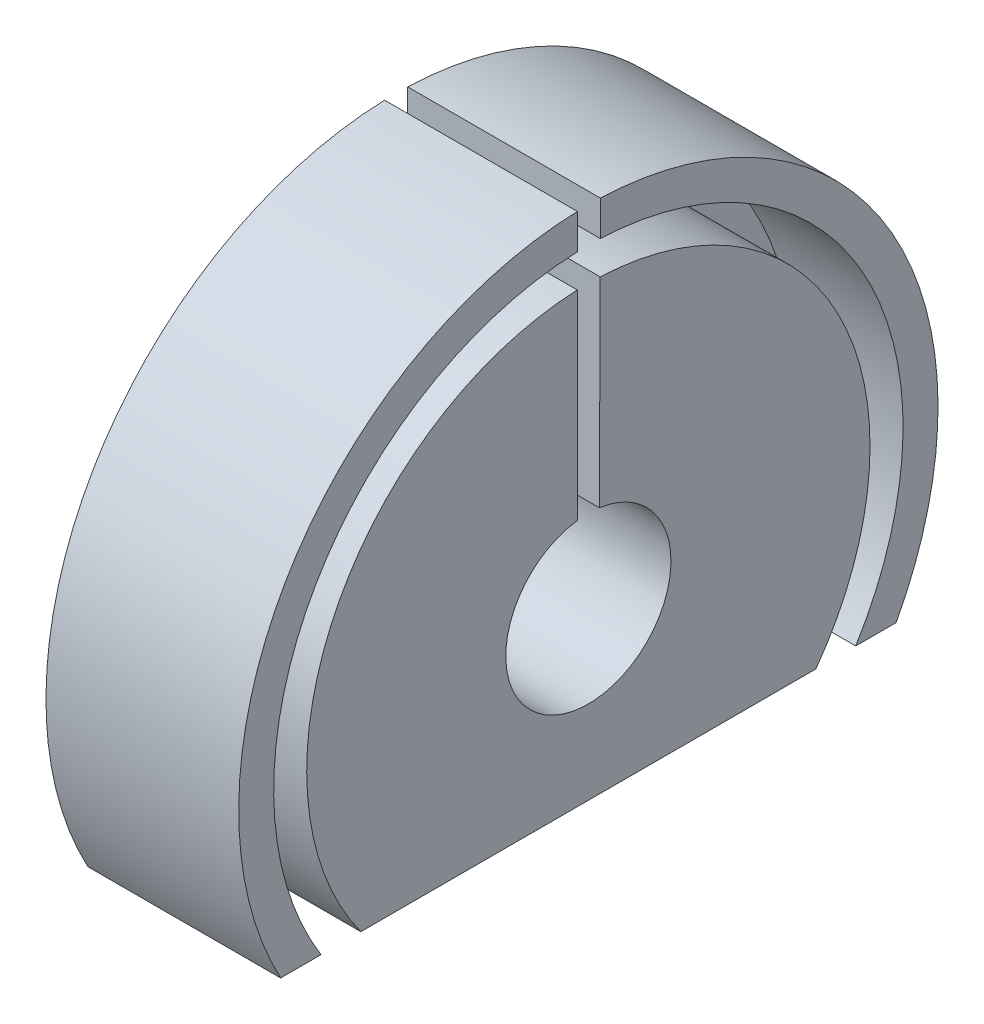
SolidWorks part; units mm, degrees
ref_plane "Front" through (0, 0, 0) normal (0, 0, 1) x (1, 0, 0)
ref_plane "Top" through (0, 0, 0) normal (0, 1, 0) x (1, 0, 0)
ref_plane "Right" through (0, 0, 0) normal (1, 0, 0) x (0, 0, -1)
sketch "Croquis1" plane through (0, 0, 0) normal (1, 0, 0) x (0, 0, -1)
  line L0 (0, 0) -> (0, 57.8) construction
  line L1 (-2, 14.8661) -> (-2, 63.4685)
  line L2 (2, 14.8661) -> (2.1972, 63.462)
  arc A0 (-2, 63.4685) -> (2.1972, 63.462) centre (0, 0) ccw
  arc A1 (-2, 14.8661) -> (2, 14.8661) centre (0, 0) ccw
  dimension "D1" = 127
  dimension "D2" = 30
  dimension "D3" = 2
extrude "Saliente-Extruir1" add sketch "Croquis1" along normal blind 35
sketch "Croquis2" plane through (35, 0, 0) normal (-1, 0, 0) x (0, 0, 1)
  circle A0 centre (0, 0) radius 57.15
  circle A2 centre (0, 0) radius 51.15
  dimension "D1" = 114.3
  dimension "D2" = 6
sketch "Croquis3" plane through (0, 0, 0) normal (-1, 0, 0) x (0, 0, 1)
  line L5 (-2.1173, 19.8876) -> (-2.1173, 43.7622)
  line L6 (12.9132, 43.7622) -> (2, 43.7622)
  line L7 (-12.9132, 43.7622) -> (-12.9132, 27.0786)
  line L8 (12.9132, 43.7622) -> (12.9132, 27.0786)
  line L9 (-2.1972, 63.462) -> (-2, 14.8661) construction
  line L10 (2, 19.8997) -> (2, 43.7622)
  line L11 (2, 14.8661) -> (2, 63.4685) construction
  line L12 (-2.1173, 43.7622) -> (-12.9132, 43.7622)
  arc A0 (-2.1173, 19.8876) -> (2, 19.8997) centre (0, 0) ccw
  arc A1 (-12.9132, 27.0786) -> (12.9132, 27.0786) centre (0, 0) ccw
  dimension "D1" = 40
  dimension "D2" = 60
extrude "Saliente-Extruir2" add sketch "Croquis3" along normal blind 12
extrude "Cortar-Extruir2" cut sketch "Croquis2" along normal blind 20
sketch "Croquis4" plane through (0, 0, 0) normal (-1, 0, 0) x (0, 0, 1)
  line L2 (-77.1974, -30.148) -> (74.517, -30.148)
  line L5 (-77.1974, -30.148) -> (-77.1974, -69.3058)
  line L6 (-77.1974, -69.3058) -> (74.517, -69.3058)
  line L7 (74.517, -30.148) -> (74.517, -69.3058)
extrude "Cortar-Extruir3" cut sketch "Croquis4" against normal up to next
hole_wizard "Taladro de margen para M31" positions "Croquis5" profile "Croquis6" hole size "M3" standard "ISO"
sketch "Croquis5" plane through (572.3145, -384.9932, -12.9132) normal (0, 0, -1) x (-1, 0, 0)
  point P0 (648.604, 421.1394)
sketch "Croquis6" plane through (-76.2895, 36.1462, -12.9132) normal (1, 0, 0) x (0, 1, 0)
  line L0 (0, 0) -> (0, 76.4132)
  line L1 (0, 76.4132) -> (1.7, 76.4132)
  line L2 (1.7, 76.4132) -> (1.7, 0)
  line L3 (1.7, 0) -> (0, 0)
  line L4 (0, -6.35) -> (0, 107.95) construction
  dimension "Diámetro de taladro hasta el siguiente" = 3.4
  dimension "Profundidad de taladro hasta el siguiente" = 76.4132
